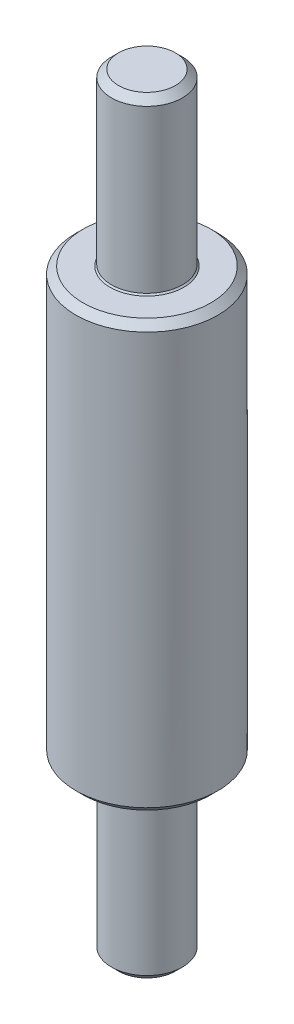
SolidWorks part; units mm, degrees
ref_plane "前视基准面" through (0, 0, 0) normal (0, 0, 1) x (1, 0, 0)
ref_plane "上视基准面" through (0, 0, 0) normal (0, 1, 0) x (1, 0, 0)
ref_plane "右视基准面" through (0, 0, 0) normal (1, 0, 0) x (0, 0, -1)
other "Configuration Table"
sketch "草图1" plane through (0, 0, 0) normal (0, 0, 1) x (1, 0, 0)
  line L0 (0, 17.9143) -> (0, -10.0949) construction
  line L1 (0, 54) -> (5, 54)
  line L2 (5, 54) -> (5, 30)
  line L3 (5, 30) -> (10, 30)
  line L4 (10, 30) -> (10, -30)
  line L5 (10, -30) -> (5, -30)
  line L6 (5, -30) -> (5, -54)
  line L7 (5, -54) -> (0, -54)
  line L8 (0, 0) -> (25.4592, 0) construction
  line L9 (0, 54) -> (0, -54)
  dimension "D1" = 5
  dimension "D2" = 10
  dimension "D3" = 60
  dimension "D4" = 24
  dimension "D5" = 24
revolve "旋转1" add sketch "草图1" angle 360 about L9
chamfer "倒角1" distance 1 angle 45 4 edges at (-10, -30, 0) (-10, 30, 0) (-5, -54, 0) (-5, 54, 0)
chamfer "倒角2" distance 0.2 angle 45 2 edges at (-5, 30, 0) (-5, -30, 0)
